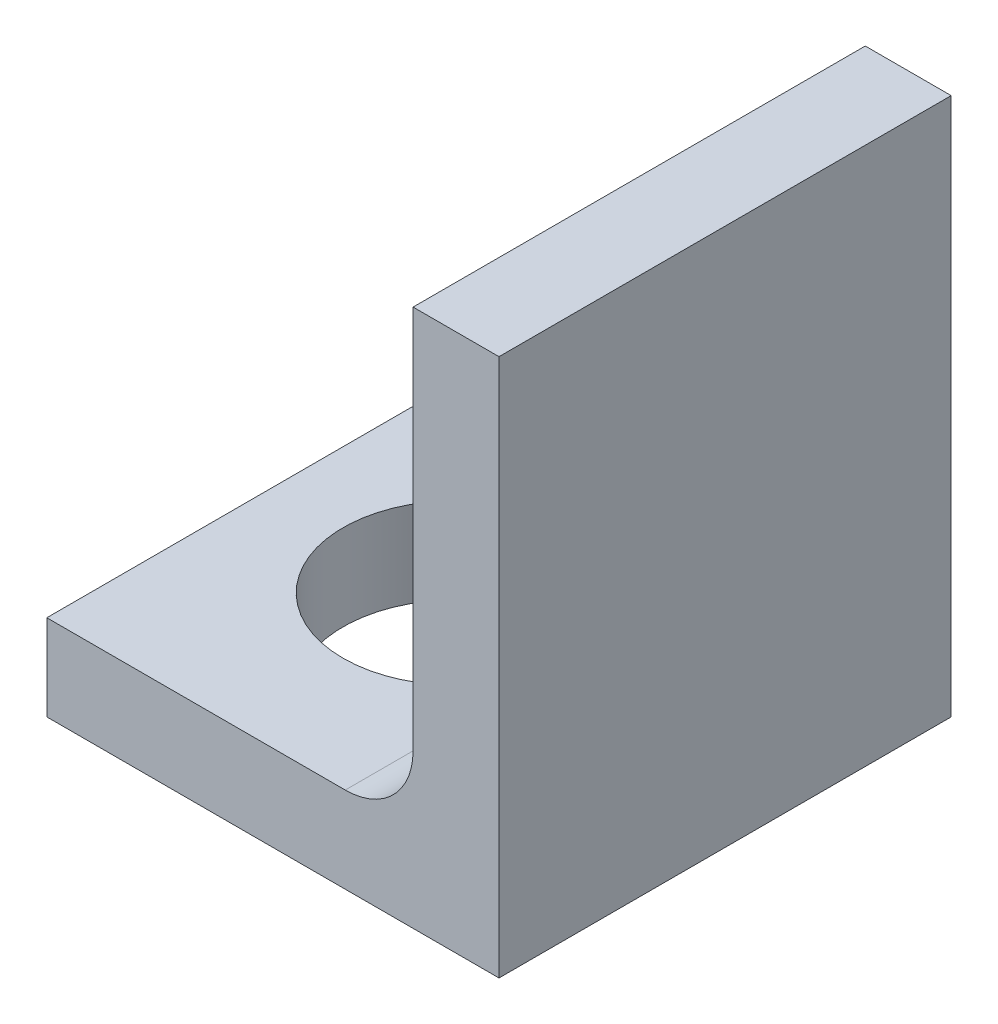
SolidWorks part; units mm, degrees
ref_plane "Front Plane" through (0, 0, 0) normal (0, 0, 1) x (1, 0, 0)
ref_plane "Top Plane" through (0, 0, 0) normal (0, 1, 0) x (1, 0, 0)
ref_plane "Right Plane" through (0, 0, 0) normal (1, 0, 0) x (0, 0, -1)
sketch "Sketch1" plane through (0, 0, 0) normal (0, 0, 1) x (1, 0, 0)
  line L1 (0, 0) -> (20, 0)
  line L2 (0, 0) -> (0, -3.8)
  line L3 (0, -3.8) -> (20, -3.8)
  line L4 (20, 0) -> (20, -3.8)
  dimension "D1" = 3.8
  dimension "D2" = 20
extrude "Boss-Extrude1" add sketch "Sketch1" along normal blind 20
sketch "Sketch2" plane through (0, 0, 0) normal (0, 1, 0) x (1, 0, 0)
  line L0 (20, -20) -> (0, -20) construction
  line L1 (20, 0) -> (16.2, 0)
  line L2 (20, 0) -> (20, -20)
  line L3 (20, -20) -> (16.2, -20)
  line L4 (16.2, 0) -> (16.2, -20)
  dimension "D1" = 3.8
extrude "Boss-Extrude2" add sketch "Sketch2" along normal blind 20
sketch "Sketch3" plane through (0, 0, 0) normal (0, 1, 0) x (1, 0, 0)
  line L0 (16.2, 0) -> (0, -20)
  circle A0 centre (8.1, -10) radius 5
  dimension "D1" = 10
extrude "Cut-Extrude1" cut sketch "Sketch3" against normal blind 30 contours A0
fillet "Fillet1" radius 3 1 edges at (16.2, 0, 10)
